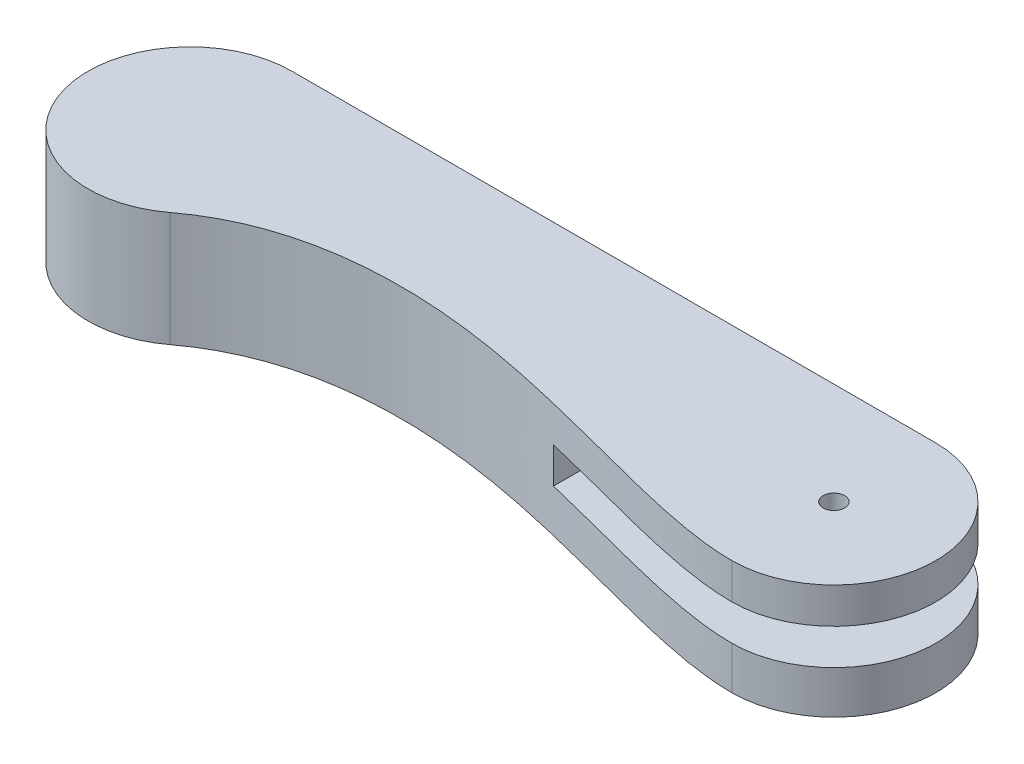
SolidWorks part; units mm, degrees
ref_plane "Front Plane" through (0, 0, 0) normal (0, 0, 1) x (1, 0, 0)
ref_plane "Top Plane" through (0, 0, 0) normal (0, 1, 0) x (1, 0, 0)
ref_plane "Right Plane" through (0, 0, 0) normal (1, 0, 0) x (0, 0, -1)
sketch "Sketch1" plane through (0, 0, 0) normal (0, 1, 0) x (1, 0, 0)
  line L0 (-45, 0) -> (45, 0) construction
  line L1 (-45, 14.25) -> (45, 14.25)
  line L2 (-45, -14.25) -> (45, -14.25)
  arc A0 (-45, 14.25) -> (-45, -14.25) centre (-45, 0) ccw
  arc A1 (45, -14.25) -> (45, 14.25) centre (45, 0) ccw
  point P3 (0, 0)
  dimension "D1" = 14.25
  dimension "D2" = 90
extrude "Boss-Extrude1" add sketch "Sketch1" along normal blind 6
sketch "Sketch2" plane through (0, 6, 0) normal (0, 1, 0) x (1, 0, 0)
  circle A0 centre (-45, 0) radius 8.25 construction
  circle A1 centre (-45, 8.25) radius 2.5
  circle A2 centre (-45, -8.25) radius 2.5
  point P9 (-45, 0)
  dimension "D1" = 16.5
  dimension "D2" = 5
  dimension "D3" = 2
extrude "Cut-Extrude1" cut sketch "Sketch2" against normal up to next
sketch "Sketch3" plane through (0, 0, 0) normal (0, -1, 0) x (1, 0, 0)
  circle A0 centre (45, 0) radius 1.5
  dimension "D1" = 3
extrude "Cut-Extrude2" cut sketch "Sketch3" against normal through all
sketch "Sketch4" plane through (0, 6, 0) normal (0, 1, 0) x (1, 0, 0)
  line L0 (-45, 14.25) -> (13.5, 14.25)
  line L1 (-45, 14.25) -> (45, 14.25) construction
  line L2 (13.5, 14.25) -> (13.5, -14.25)
  line L3 (-45, -14.25) -> (45, -14.25) construction
  line L4 (13.5, -14.25) -> (-45, -14.25)
  arc A0 (-45, 14.25) -> (-45, -14.25) centre (-45, 0) ccw
  arc A1 (-45, 14.25) -> (-45, -14.25) centre (-45, 0) ccw construction
  dimension "D1" = 58.5
extrude "Boss-Extrude2" add sketch "Sketch4" along normal blind 5
sketch "Sketch5" plane through (0, 11, 0) normal (0, 1, 0) x (1, 0, 0)
  line L0 (-45, 0) -> (45, 0) construction
  line L1 (-45, 14.25) -> (45, 14.25)
  line L2 (-45, -14.25) -> (45, -14.25)
  arc A0 (-45, 14.25) -> (-45, -14.25) centre (-45, 0) ccw
  arc A1 (45, -14.25) -> (45, 14.25) centre (45, 0) ccw
  point P4 (0, 0)
  dimension "D1" = 14.25
extrude "Boss-Extrude3" add sketch "Sketch5" along normal blind 5
sketch "Sketch6" plane through (0, 16, 0) normal (0, 1, 0) x (1, 0, 0)
  circle A0 centre (45, 0) radius 1.5
  dimension "D1" = 3
extrude "Cut-Extrude3" cut sketch "Sketch6" against normal up to next
sketch "Sketch7" plane through (0, 16, 0) normal (0, 1, 0) x (1, 0, 0)
  line L0 (0, -6.05) -> (0, 6.05) construction
  line L1 (-45, -14.25) -> (45, -14.25)
  circle A0 centre (-45, 0) radius 14.25
  circle A1 centre (45, 0) radius 14.25
  spline S0 degree 3 poles (-36.414, -11.3729) (-26.8004, -4.1151) (3.015, -1.8878) (33.8974, -14.25) (45, -14.25) knots 0 0 0 0 0.445882 1 1 1 1
  line M5 (-45, -14.25) -> (45, -14.25)
extrude "Cut-Extrude4" cut sketch "Sketch7" against normal up to next contours S0 A0 M5
equation "\"Length\"= 90mm"
equation "\"Radius\"= 14.25mm"
equation "\"Thick\"= 6mm"
equation "\"D1@Sketch1\"= \"Radius\""
equation "\"D2@Sketch1\" = \"Length\""
equation "\"D1@Boss-Extrude1\"= \"Thick\""
equation "\"D1@Sketch4\"=\"Length\"*0.65"
equation "\"D1@Sketch5\"=\"Radius\""
